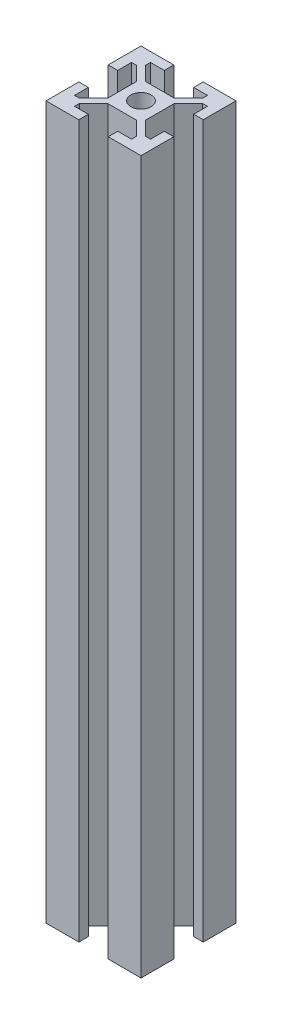
SolidWorks part; units mm, degrees
ref_plane "Front" through (0, 0, 0) normal (0, 0, 1) x (1, 0, 0)
ref_plane "Top" through (0, 0, 0) normal (0, 1, 0) x (1, 0, 0)
ref_plane "Right" through (0, 0, 0) normal (1, 0, 0) x (0, 0, -1)
sketch "스케치1" plane through (0, 0, 0) normal (0, 1, 0) x (1, 0, 0)
  line L0 (3.1, 8) -> (6, 8)
  line L1 (-10.001, 9.999) -> (-3.1, 9.999)
  line L2 (-10.001, 9.999) -> (-10.001, 3.1)
  line L3 (-10.001, -9.999) -> (-3.1, -9.999)
  line L4 (10.001, 9.999) -> (10.001, 3.1)
  line L5 (-10.001, 9.999) -> (-1.5204, 1.5201) construction
  line L6 (-10.001, -9.999) -> (-1.5204, -1.5201) construction
  line L11 (-7, -7) -> (-1.5203, -1.5203) construction
  line L12 (-7, 7) -> (-1.5203, 1.5203) construction
  line L15 (-3.1, 9.999) -> (-3.1, 8)
  line L17 (3.1, 9.999) -> (3.1, 8)
  line L18 (8, -3.1) -> (8, -6)
  line L27 (-3.1, 8) -> (-6, 8)
  line L28 (6, 8) -> (6, 7)
  line L30 (0, 4) -> (3, 4)
  line L31 (3, 4) -> (6, 7)
  line L32 (-6, 8) -> (-6, 7)
  line L33 (-6, 7) -> (-3, 4)
  line L34 (0, 4) -> (-3, 4)
  line L35 (3.1, 9.999) -> (10.001, 9.999)
  line L36 (10.001, 3.1) -> (8, 3.1)
  line L37 (10.001, -3.1) -> (8, -3.1)
  line L38 (8, 3.1) -> (8, 6)
  line L39 (8, -6) -> (7, -6)
  line L40 (4, 0) -> (4, -3)
  line L41 (4, -3) -> (7, -6)
  line L42 (8, 6) -> (7, 6)
  line L43 (7, 6) -> (4, 3)
  line L44 (4, 0) -> (4, 3)
  line L45 (-3.1, -8) -> (-6, -8)
  line L47 (3.1, -9.999) -> (3.1, -8)
  line L48 (-3.1, -9.999) -> (-3.1, -8)
  line L49 (3.1, -8) -> (6, -8)
  line L50 (-6, -8) -> (-6, -7)
  line L51 (0, -4) -> (-3, -4)
  line L52 (-3, -4) -> (-6, -7)
  line L53 (6, -8) -> (6, -7)
  line L54 (6, -7) -> (3, -4)
  line L55 (0, -4) -> (3, -4)
  line L56 (-8, 3.1) -> (-8, 6)
  line L58 (-10.001, -3.1) -> (-8, -3.1)
  line L59 (-10.001, 3.1) -> (-8, 3.1)
  line L60 (-8, -3.1) -> (-8, -6)
  line L61 (-8, 6) -> (-7, 6)
  line L62 (-4, 0) -> (-4, 3)
  line L63 (-4, 3) -> (-7, 6)
  line L64 (-8, -6) -> (-7, -6)
  line L65 (-7, -6) -> (-4, -3)
  line L66 (-4, 0) -> (-4, -3)
  line L67 (-10.001, -3.1) -> (-10.001, -9.999)
  line L69 (3.1, -9.999) -> (10.001, -9.999)
  line L72 (10.001, -3.1) -> (10.001, -9.999)
  line L73 (1.5203, -1.5203) -> (7, -7) construction
  line L74 (1.5204, -1.5201) -> (10.001, -9.999) construction
  line L75 (1.5203, 1.5203) -> (7, 7) construction
  line L76 (1.5204, 1.5201) -> (10.001, 9.999) construction
  circle A4 centre (0, 0) radius 2.15
  point P0 (0, 0)
  point P6 (0, 0)
  point P21 (0, 0)
  point P22 (0, 10)
  point P31 (0, 0)
  point P40 (10, 0)
  point P46 (0, 0)
  point P53 (0, -10)
  point P59 (0, 0)
  point P66 (-10, 0)
  point P72 (0, 0)
  dimension "D1" = 4
extrude "보스-돌출1" add sketch "스케치1" along normal blind 150
sketch "스케치3" plane through (10.001, 0, 0) normal (1, 0, 0) x (0, 0, -1)
  line L0 (0, 0) -> (0, 150) construction
  line L1 (-3, 150) -> (3, 150) construction
  circle A0 centre (0, 75) radius 3
extrude "컷-돌출1" cut sketch "스케치3" against normal blind 26
